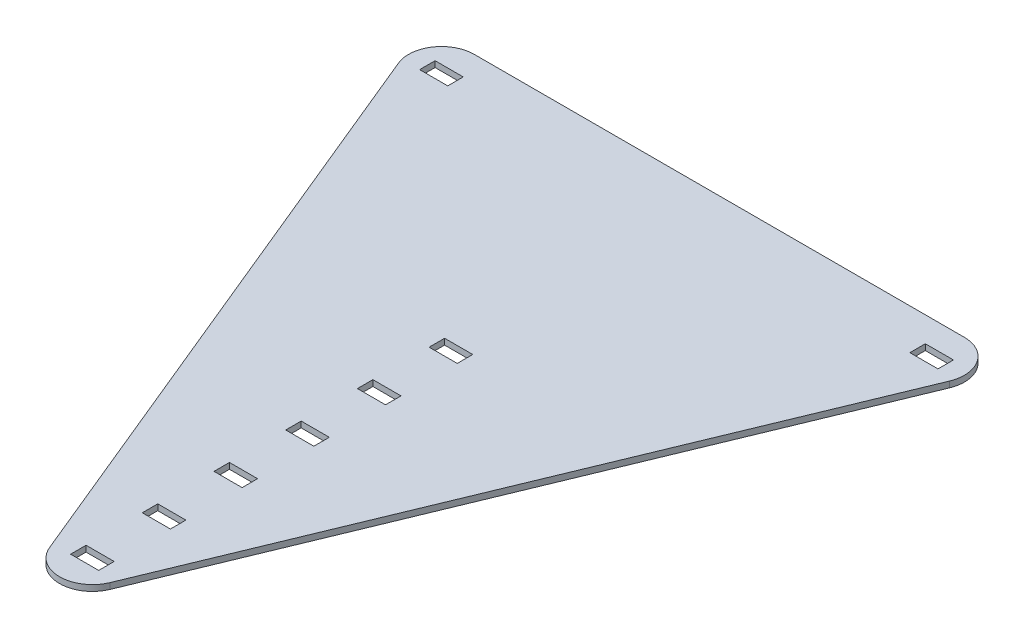
SolidWorks part; units mm, degrees
ref_plane "Front Plane" through (0, 0, 0) normal (0, 0, 1) x (1, 0, 0)
ref_plane "Top Plane" through (0, 0, 0) normal (0, 1, 0) x (1, 0, 0)
ref_plane "Right Plane" through (0, 0, 0) normal (1, 0, 0) x (0, 0, -1)
sketch "Sketch1" plane through (0, 0, 0) normal (0, 1, 0) x (1, 0, 0)
  line L0 (32.3547, -13.348) -> (293.8597, 620.522)
  line L1 (0, 0) -> (0, 668.87) construction
  line L2 (-261.505, 668.87) -> (261.505, 668.87)
  line L3 (-15, 68.25) -> (-15, 84.75)
  line L4 (246.505, 625.62) -> (276.505, 625.62)
  line L5 (246.505, 625.62) -> (246.505, 642.12)
  line L6 (246.505, 642.12) -> (276.505, 642.12)
  line L7 (276.505, 625.62) -> (276.505, 642.12)
  line L8 (246.505, 625.62) -> (276.505, 642.12) construction
  line L9 (246.505, 642.12) -> (276.505, 625.62) construction
  line L10 (-15, -8.25) -> (15, -8.25)
  line L11 (-15, -8.25) -> (-15, 8.25)
  line L12 (-15, 8.25) -> (15, 8.25)
  line L13 (15, -8.25) -> (15, 8.25)
  line L14 (-15, -8.25) -> (15, 8.25) construction
  line L15 (-15, 8.25) -> (15, -8.25) construction
  line L16 (-15, 68.25) -> (15, 68.25)
  line L17 (15, 68.25) -> (15, 84.75)
  line L18 (-15, 84.75) -> (15, 84.75)
  line L19 (-15, 144.75) -> (-15, 161.25)
  line L20 (-15, 144.75) -> (15, 144.75)
  line L21 (15, 144.75) -> (15, 161.25)
  line L22 (-15, 161.25) -> (15, 161.25)
  line L23 (-15, 221.25) -> (-15, 237.75)
  line L24 (-15, 221.25) -> (15, 221.25)
  line L25 (15, 221.25) -> (15, 237.75)
  line L26 (-15, 237.75) -> (15, 237.75)
  line L27 (-15, 297.75) -> (-15, 314.25)
  line L28 (-15, 297.75) -> (15, 297.75)
  line L29 (15, 297.75) -> (15, 314.25)
  line L30 (-15, 314.25) -> (15, 314.25)
  line L31 (-15, 374.25) -> (-15, 390.75)
  line L32 (-15, 374.25) -> (15, 374.25)
  line L33 (15, 374.25) -> (15, 390.75)
  line L34 (-15, 390.75) -> (15, 390.75)
  line L35 (-32.3547, -13.348) -> (-293.8597, 620.522)
  line L36 (-246.505, 642.12) -> (-276.505, 642.12)
  line L37 (-276.505, 625.62) -> (-276.505, 642.12)
  line L38 (-246.505, 625.62) -> (-276.505, 625.62)
  line L39 (-246.505, 625.62) -> (-246.505, 642.12)
  circle A0 centre (0, 0) radius 35 construction
  circle A1 centre (261.505, 633.87) radius 35 construction
  arc A3 (261.505, 668.87) -> (293.8597, 620.522) centre (261.505, 633.87) cw
  arc A4 (-261.505, 668.87) -> (-293.8597, 620.522) centre (-261.505, 633.87) ccw
  arc A5 (-32.3547, -13.348) -> (32.3547, -13.348) centre (0, 0) ccw
  dimension "D1" = 30
  dimension "D5" = 70
  dimension "D6" = 70
  dimension "D2" = 16.5
  dimension "D3" = 246.505
  dimension "D4" = 617.37
  dimension "D7" = 16.5
  dimension "D8" = 30
  dimension "D10" = 60
  dimension "D9" = 6
extrude "Boss-Extrude1" add sketch "Sketch1" along normal blind 6.35
